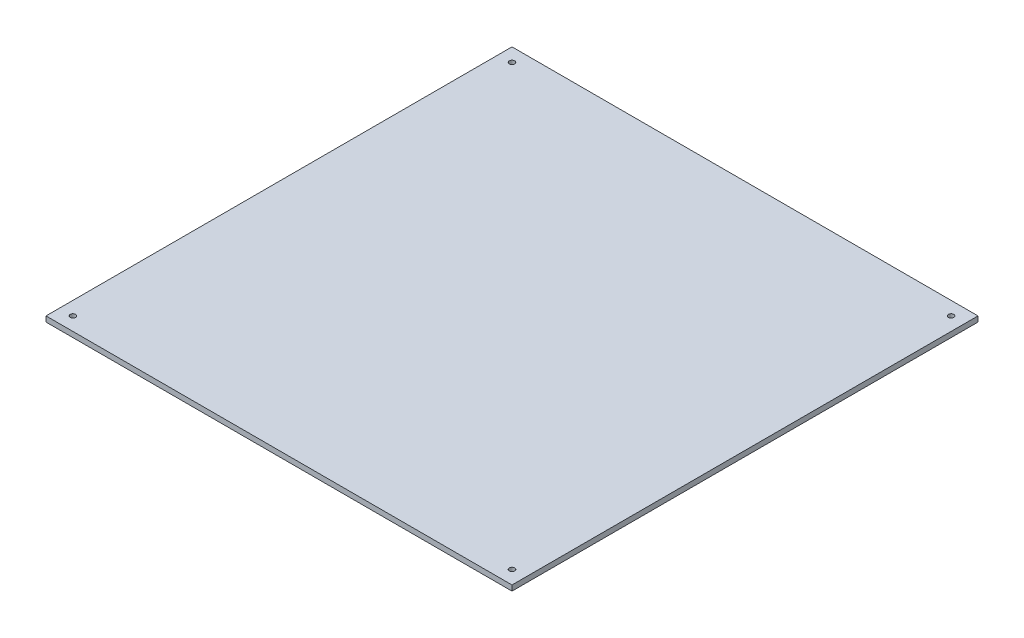
SolidWorks part; units mm, degrees
material "Balsa"
ref_plane "Plano frontal" through (0, 0, 0) normal (0, 0, 1) x (1, 0, 0)
ref_plane "Plano superior" through (0, 0, 0) normal (0, 1, 0) x (1, 0, 0)
ref_plane "Plano direito" through (0, 0, 0) normal (1, 0, 0) x (0, 0, -1)
sketch "Esboço1" plane through (0, 0, 0) normal (0, 1, 0) x (1, 0, 0)
  line L0 (-122.5, -122.5) -> (-122.5, 122.5) construction
  line L1 (-130, -130) -> (130, -130)
  line L2 (-130, -130) -> (-130, 130)
  line L3 (-130, 130) -> (130, 130)
  line L4 (130, -130) -> (130, 130)
  line L5 (-130, -130) -> (130, 130) construction
  line L6 (-130, 130) -> (130, -130) construction
  line L7 (0, 130) -> (0, -130) construction
  line L8 (122.5, -122.5) -> (122.5, 122.5) construction
  line L11 (-130, 0) -> (130, 0) construction
  circle A0 centre (-122.5, 122.5) radius 1.5
  circle A1 centre (-122.5, -122.5) radius 1.5
  circle A2 centre (122.5, -122.5) radius 1.5
  circle A3 centre (122.5, 122.5) radius 1.5
  point P0 (0, 0)
  point P12 (-122.5, 0)
  dimension "D4" = 3
  dimension "D1" = 260
  dimension "D2" = 260
  dimension "D5" = 7.5
  dimension "D3" = 7.5
extrude "Ressalto-extrusão1" add sketch "Esboço1" along normal blind 3
equation "\"D1@Esboço1\"=\"D2@Esboço1\""
